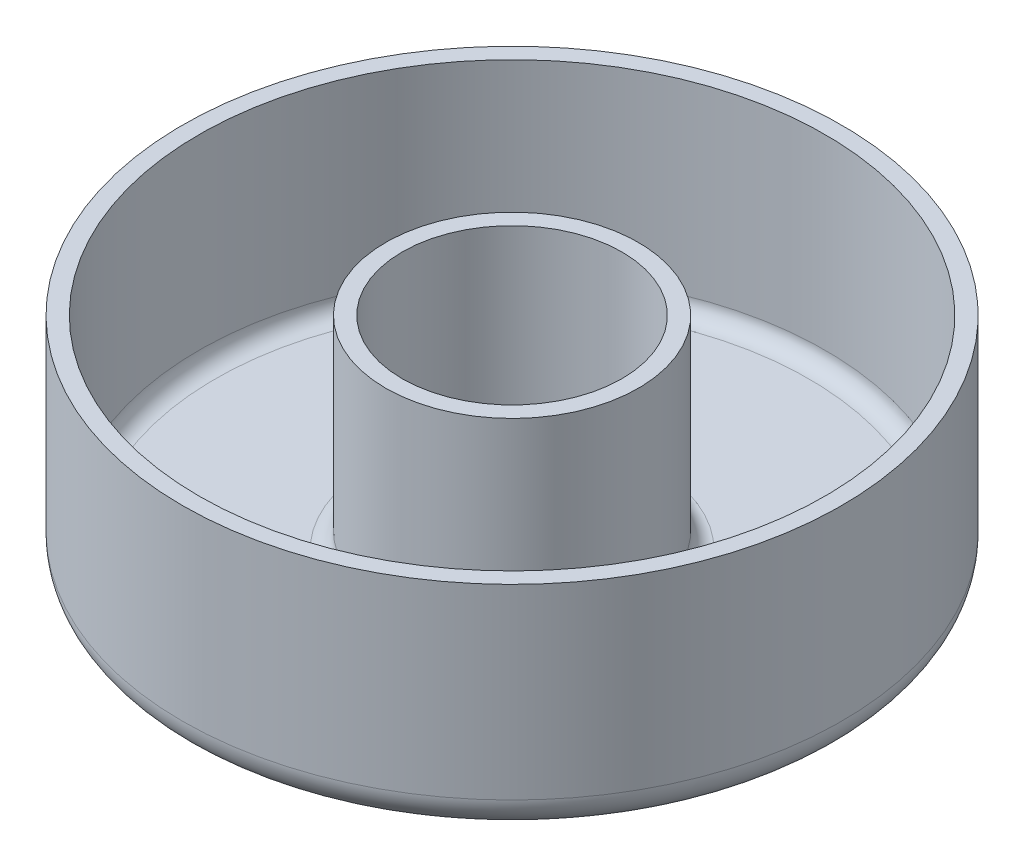
SolidWorks part; units mm, degrees
ref_plane "Front Plane" through (0, 0, 0) normal (0, 0, 1) x (1, 0, 0)
ref_plane "Top Plane" through (0, 0, 0) normal (0, 1, 0) x (1, 0, 0)
ref_plane "Right Plane" through (0, 0, 0) normal (1, 0, 0) x (0, 0, -1)
sketch "Sketch2" plane through (0, 0, 0) normal (1, 0, 0) x (0, 0, -1)
  line L0 (0, 14.8724) -> (0, -9.7524) construction
  line L1 (-5, 4.25) -> (-5, -4.25)
  line L2 (-6.5, -5.75) -> (-13.5, -5.75)
  line L3 (-15, -4.25) -> (-15, 4.25)
  line L4 (-5.75, 4.25) -> (-5.75, -4.25)
  line L5 (-6.5, -5) -> (-13.5, -5)
  line L6 (-14.25, -4.25) -> (-14.25, 4.25)
  line L7 (-15, 4.25) -> (-14.25, 4.25)
  line L8 (-5.75, 4.25) -> (-5, 4.25)
  arc A0 (-15, -4.25) -> (-13.5, -5.75) centre (-13.5, -4.25) ccw
  arc A1 (-5, -4.25) -> (-6.5, -5.75) centre (-6.5, -4.25) cw
  arc A2 (-5.75, -4.25) -> (-6.5, -5) centre (-6.5, -4.25) cw
  arc A3 (-14.25, -4.25) -> (-13.5, -5) centre (-13.5, -4.25) ccw
  point P5 (-5, 0)
  dimension "D3" = 1.5
  dimension "D1" = 10
  dimension "D2" = 30
  dimension "D5" = 10
  dimension "D4" = 0.75
revolve "Revolve1" add sketch "Sketch2" angle 360 about L0
